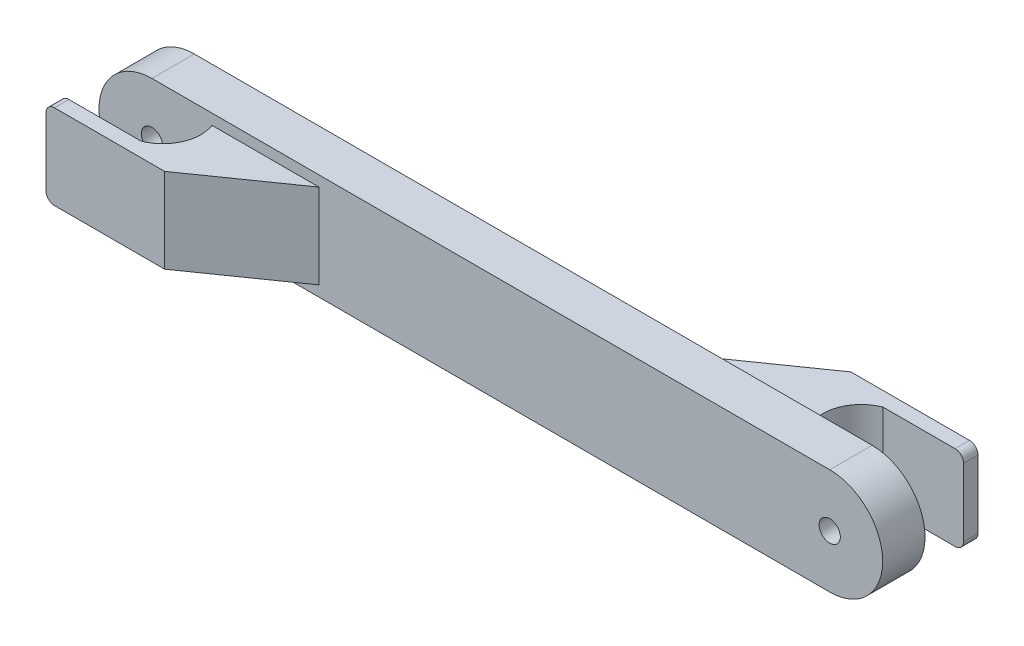
SolidWorks part; units mm, degrees
ref_plane "Front" through (0, 0, 0) normal (0, 0, 1) x (1, 0, 0)
ref_plane "Top" through (0, 0, 0) normal (0, 1, 0) x (1, 0, 0)
ref_plane "Right" through (0, 0, 0) normal (1, 0, 0) x (0, 0, -1)
sketch "Sketch1" plane through (0, 0, 0) normal (0, 0, 1) x (1, 0, 0)
  line L0 (299.8703, -79.0606) -> (503.0703, -79.0606) construction
  line L1 (299.8703, -63.1856) -> (503.0703, -63.1856)
  line L2 (299.8703, -94.9356) -> (503.0703, -94.9356)
  line L3 (401.4703, -94.9356) -> (401.4703, -63.1856) construction
  arc A0 (299.8703, -63.1856) -> (299.8703, -94.9356) centre (299.8703, -79.0606) ccw
  arc A1 (503.0703, -94.9356) -> (503.0703, -63.1856) centre (503.0703, -79.0606) ccw
  circle A2 centre (299.8703, -79.0606) radius 3.175
  circle A3 centre (503.0703, -79.0606) radius 3.175
  point P2 (401.4703, -79.0606)
  dimension "D1" = 203.2
  dimension "D2" = 15.875
  dimension "D3" = 31.75
extrude "Boss-Extrude1" add sketch "Sketch1" along normal blind 12.7
sketch "Sketch2" plane through (0, 0, 0) normal (0, 0, -1) x (-1, 0, 0)
  line L5 (-477.6703, -66.3606) -> (-477.6703, -91.7606)
  line L6 (-513.2303, -91.7606) -> (-477.6703, -91.7606)
  line L7 (-515.7703, -89.2206) -> (-515.7703, -68.9006)
  line L8 (-513.2303, -66.3606) -> (-477.6703, -66.3606)
  line L10 (-515.7703, -91.7606) -> (-490.3703, -66.3606) construction
  line L11 (-515.7703, -66.3606) -> (-490.3703, -91.7606) construction
  arc A0 (-513.2303, -91.7606) -> (-515.7703, -89.2206) centre (-513.2303, -89.2206) cw
  arc A3 (-515.7703, -68.9006) -> (-513.2303, -66.3606) centre (-513.2303, -68.9006) cw
  point P0 (-503.0703, -79.0606)
  dimension "D3" = 2.54
  dimension "D1" = 25.4
  dimension "D2" = 25.4
  dimension "D4" = 35.56
extrude "Boss-Extrude2" add sketch "Sketch2" along normal blind 19.05
sketch "Sketch4" plane through (0, -91.7606, 0) normal (0, -1, 0) x (1, 0, 0)
  line L0 (477.6703, -19.05) -> (450.464, 0)
  line L1 (299.8703, 0) -> (503.0703, 0) construction
  line L2 (450.464, 0) -> (477.6703, 0)
  line L3 (477.6703, 0) -> (477.6703, -19.05)
  dimension "D2" = 19.05
  dimension "D4" = 27.2062
  dimension "D1" = 215
  dimension "D3" = 33.2127
sketch "Sketch6" plane through (0, -91.7606, 0) normal (0, -1, 0) x (1, 0, 0)
  line L1 (515.7703, -19.05) -> (515.7703, 0) construction
  line L2 (499.2461, 0) -> (515.7703, 0)
  line L3 (512.5953, 0) -> (477.6703, 0) construction
  line L6 (491.6403, -14.7335) -> (515.7703, -14.7335)
  line L7 (515.7703, -14.7335) -> (515.7703, 0)
  line L10 (299.8703, 0) -> (503.0703, 0) construction
  line L11 (512.5953, 0) -> (477.6703, 0) construction
  line L12 (485.0369, 0) -> (488.9084, 0)
  line L13 (488.9084, 0) -> (499.2461, 0)
  arc A2 (491.6403, -14.7335) -> (485.0369, 0) centre (495.7053, -4.0651) cw
  point P1 (0, 0)
  point P10 (485.0369, 0)
  point P18 (0, 0)
  dimension "D2" = 11.4166
  dimension "D1" = 24.13
  dimension "D3" = 30.7333
  dimension "D4" = 14.7335
extrude "Cut-Extrude2" cut sketch "Sketch6" against normal blind 30.48
extrude "Boss-Extrude7" add sketch "Sketch4" against normal blind 25.4
ref_plane "Plane5" through (401.447, 0, 0) normal (1, 0, 0) x (0, 0, -1)
ref_plane "Plane6" through (401.4703, 0, 0) normal (1, 0, 0) x (0, 0, -1)
ref_plane "Plane7" through (0, 0, 6.3485) normal (0, 0, 1) x (1, 0, 0)
surface "Surface-MidSurface2" parameters "D0"=50000
sketch "Sketch7" plane through (0, 0, 12.7) normal (0, 0, 1) x (1, 0, 0)
  line L0 (310.0303, -66.3606) -> (312.5703, -66.3606)
  line L1 (289.7103, -91.7606) -> (310.0303, -91.7606)
  line L2 (287.1703, -89.2206) -> (287.1703, -68.9006)
  line L3 (289.7103, -66.3606) -> (310.0303, -66.3606)
  line L5 (287.1703, -91.7606) -> (312.5703, -66.3606) construction
  line L6 (287.1703, -66.3606) -> (312.5703, -91.7606) construction
  line L7 (312.5703, -66.3606) -> (322.7303, -66.3606)
  line L8 (322.7303, -66.3606) -> (322.7303, -91.7606)
  line L9 (310.0303, -91.7606) -> (322.7303, -91.7606)
  arc A0 (289.7103, -91.7606) -> (287.1703, -89.2206) centre (289.7103, -89.2206) cw
  arc A3 (287.1703, -68.9006) -> (289.7103, -66.3606) centre (289.7103, -68.9006) cw
  point P0 (299.8703, -79.0606)
  dimension "D3" = 2.54
  dimension "D1" = 25.4
  dimension "D2" = 25.4
  dimension "D4" = 10.16
extrude "Boss-Extrude8" add sketch "Sketch7" along normal blind 19.05
sketch "Sketch8" plane through (0, -66.3606, 0) normal (0, 1, 0) x (1, 0, 0)
  line L0 (287.1703, -12.7) -> (317.9043, -12.7)
  line L1 (503.0703, -12.7) -> (299.8703, -12.7) construction
  line L2 (287.1703, -12.7) -> (287.1703, -27.432)
  line L3 (287.1703, -31.75) -> (287.1703, -12.7) construction
  line L4 (287.1703, -27.432) -> (311.3003, -27.432)
  arc A0 (317.9043, -12.7) -> (311.3003, -27.432) centre (307.218, -16.7558) cw
  dimension "D1" = 30.734
  dimension "D2" = 14.732
  dimension "D3" = 24.13
extrude "Cut-Extrude3" cut sketch "Sketch8" against normal blind 41.148
sketch "Sketch9" plane through (0, -66.3606, 0) normal (0, 1, 0) x (1, 0, 0)
  line L0 (322.7303, -31.75) -> (349.9365, -12.7)
  line L1 (503.0703, -12.7) -> (299.8703, -12.7) construction
  line L4 (322.7303, -12.7) -> (349.9365, -12.7)
  line L5 (322.7303, -31.75) -> (322.7303, -12.7)
  dimension "D1" = 35
extrude "Boss-Extrude9" add sketch "Sketch9" against normal blind 25.4
